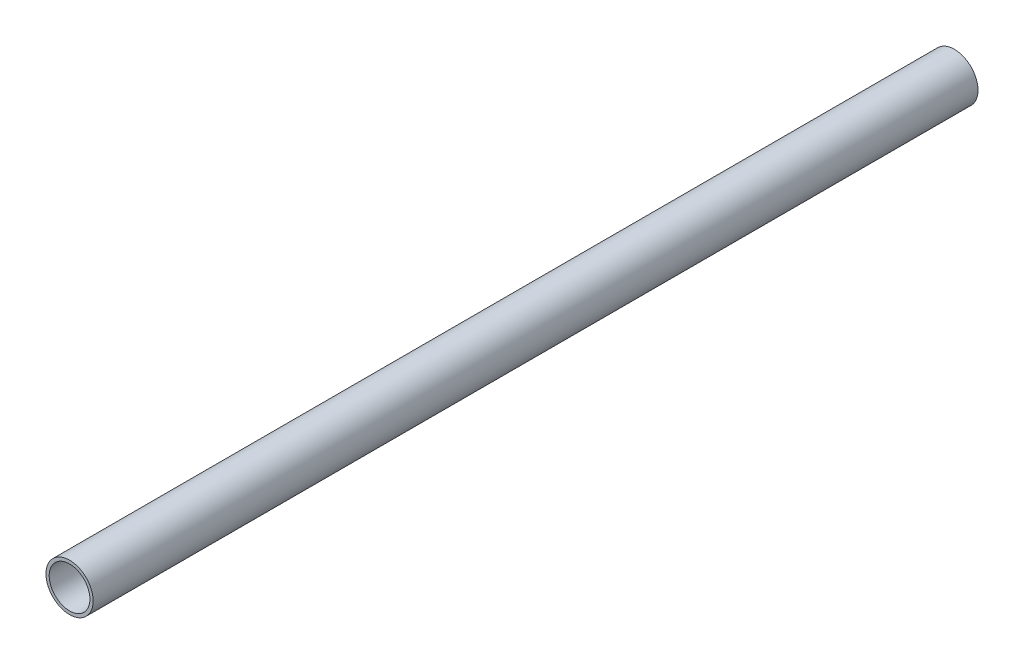
SolidWorks part; units mm, degrees
ref_plane "Front Plane" through (0, 0, 0) normal (0, 0, 1) x (1, 0, 0)
ref_plane "Top Plane" through (0, 0, 0) normal (0, 1, 0) x (1, 0, 0)
ref_plane "Right Plane" through (0, 0, 0) normal (1, 0, 0) x (0, 0, -1)
sketch "Sketch1" plane through (0, 0, 0) normal (0, 0, 1) x (1, 0, 0)
  circle A0 centre (0, 0) radius 8
  circle A1 centre (0, 0) radius 6.9
  dimension "D1" = 16
  dimension "D2" = 13.8
extrude "Boss-Extrude1" add sketch "Sketch1" along normal blind 300
